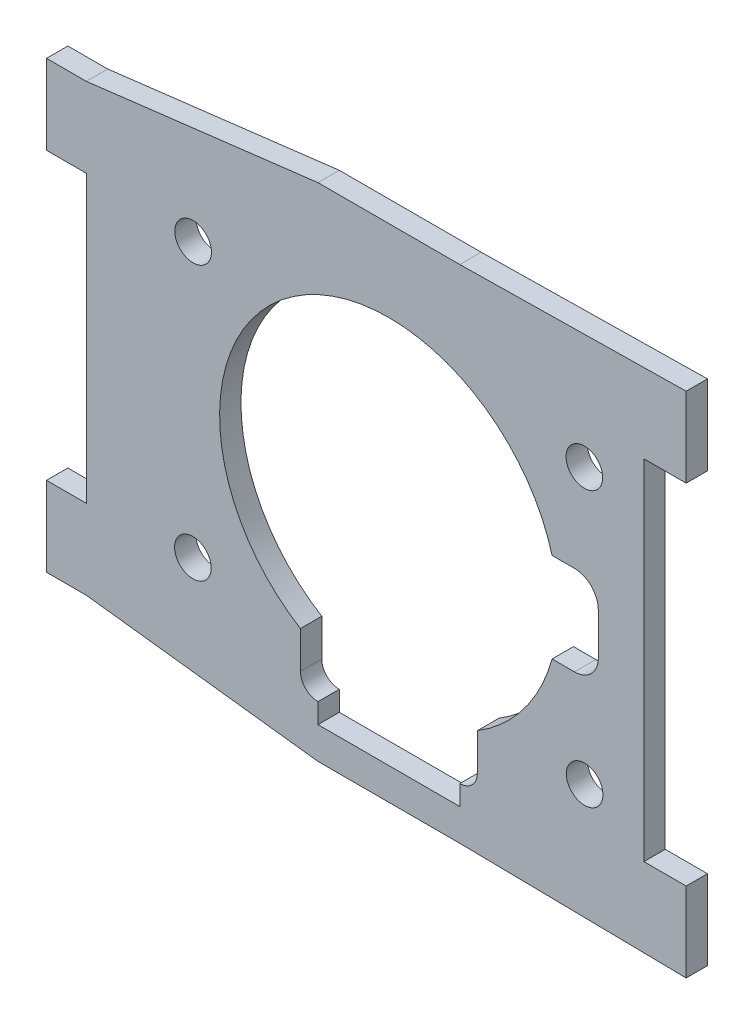
SolidWorks part; units mm, degrees
ref_plane "Front Plane" through (0, 0, 0) normal (0, 0, 1) x (1, 0, 0)
ref_plane "Top Plane" through (0, 0, 0) normal (0, 1, 0) x (1, 0, 0)
ref_plane "Right Plane" through (0, 0, 0) normal (1, 0, 0) x (0, 0, -1)
sketch "Sketch1" plane through (0, 0, 0) normal (0, 0, 1) x (1, 0, 0)
  line L0 (6343.4604, 3531.9182) -> (6343.4603, 3538.6182)
  line L1 (6339.6665, 3542.4119) -> (6336.0954, 3542.4118)
  line L2 (6295.9677, 3512.2582) -> (6295.9678, 3506.3556)
  line L3 (6298.7617, 3500.3869) -> (6321.3809, 3500.3873)
  line L4 (6298.7618, 3495.3069) -> (6321.381, 3495.3073)
  line L5 (6324.1745, 3506.3561) -> (6324.1744, 3512.2587)
  line L6 (6336.0956, 3528.1243) -> (6339.6667, 3528.1244)
  line L7 (6321.3809, 3500.3873) -> (6321.3808, 3503.5623)
  line L8 (6298.7617, 3500.3869) -> (6298.7616, 3503.5619)
  line L9 (6261.8316, 3558.0514) -> (6261.8316, 3512.4838)
  line L10 (6350.7316, 3563.0806) -> (6350.7316, 3507.4546)
  line L11 (6255.4816, 3512.4838) -> (6261.8316, 3512.4838)
  line L12 (6255.4816, 3512.4838) -> (6255.4816, 3499.7838)
  line L13 (6255.4816, 3558.0514) -> (6261.8316, 3558.0514)
  line L14 (6255.4816, 3558.0514) -> (6255.4816, 3570.7514)
  line L15 (6357.4702, 3507.4546) -> (6350.7316, 3507.4546)
  line L16 (6357.4702, 3507.4546) -> (6357.4702, 3494.7546)
  line L17 (6357.4702, 3563.0806) -> (6350.7316, 3563.0806)
  line L18 (6357.4702, 3563.0806) -> (6357.4702, 3575.7806)
  line L19 (6298.7618, 3495.3069) -> (6261.8316, 3499.7838)
  line L20 (6261.8316, 3499.7838) -> (6255.4816, 3499.7838)
  line L21 (6321.381, 3495.3073) -> (6357.4702, 3494.7546)
  line L22 (6298.7618, 3575.2284) -> (6321.381, 3575.228)
  line L23 (6298.7618, 3575.2284) -> (6261.8316, 3570.7514)
  line L24 (6321.381, 3575.228) -> (6357.4702, 3575.7806)
  line L25 (6255.4816, 3570.7514) -> (6261.8316, 3570.7514)
  arc A0 (6324.1744, 3512.2587) -> (6336.0956, 3528.1243) centre (6310.0707, 3535.2676) ccw
  arc A1 (6336.0954, 3542.4118) -> (6295.9677, 3512.2582) centre (6310.0707, 3535.2676) ccw
  arc A2 (6343.4603, 3538.6182) -> (6339.6665, 3542.4119) centre (6339.6666, 3538.6181) ccw
  arc A3 (6295.9678, 3506.3556) -> (6298.7616, 3503.5619) centre (6298.7616, 3506.3556) ccw
  arc A4 (6321.3808, 3503.5623) -> (6324.1745, 3506.3561) centre (6321.3808, 3506.356) ccw
  arc A5 (6339.6667, 3528.1244) -> (6343.4604, 3531.9182) centre (6339.6667, 3531.9181) ccw
  circle A6 centre (6278.8202, 3513.4727) radius 2.921
  circle A7 centre (6341.2804, 3513.4144) radius 2.921
  circle A8 centre (6341.2388, 3557.1802) radius 2.921
  circle A9 centre (6278.861, 3557.1209) radius 2.921
extrude "Boss-Extrude1" add sketch "Sketch1" along normal blind 3.4036
